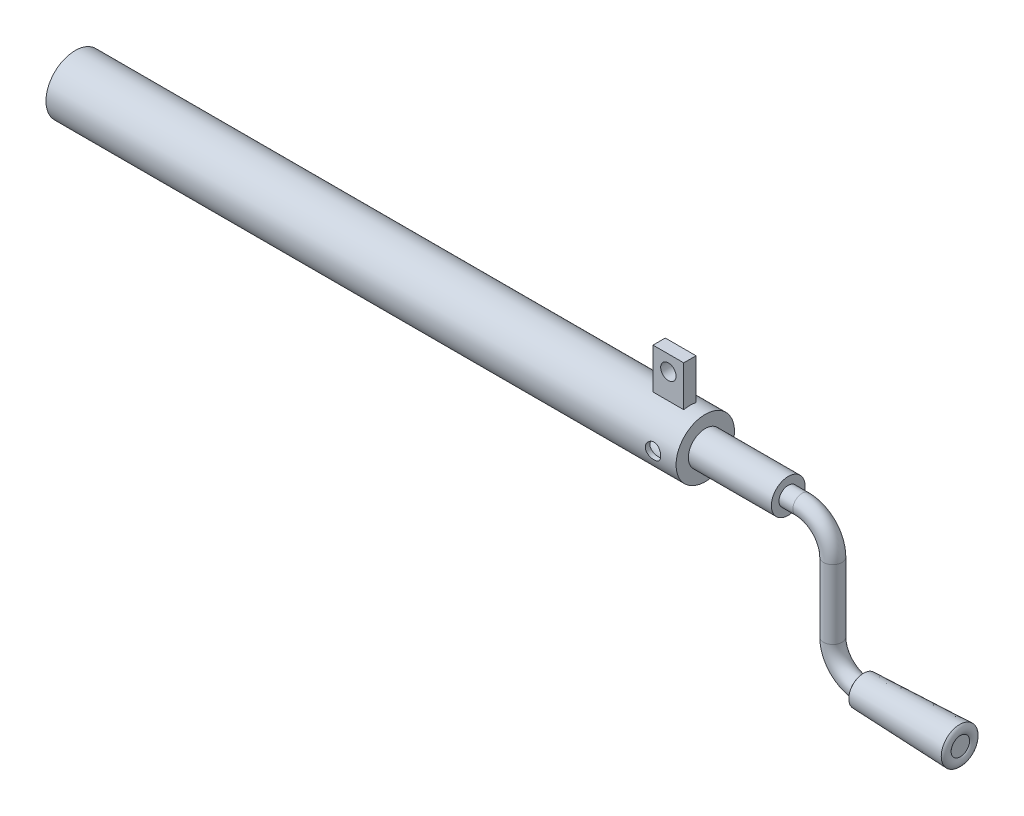
SolidWorks part; units mm, degrees
ref_plane "Front Plane" through (0, 0, 0) normal (0, 0, 1) x (1, 0, 0)
ref_plane "Top Plane" through (0, 0, 0) normal (0, 1, 0) x (1, 0, 0)
ref_plane "Right Plane" through (0, 0, 0) normal (1, 0, 0) x (0, 0, -1)
sketch "Sketch1" plane through (0, 0, 0) normal (1, 0, 0) x (0, 0, -1)
  circle A0 centre (0, 0) radius 19
  circle A1 centre (0, 0) radius 16
  dimension "D1" = 38
  dimension "D2" = 32
extrude "Boss-Extrude1" add sketch "Sketch1" along normal blind 410
sketch "Sketch2" plane through (0, 0, 0) normal (0, 0, 1) x (1, 0, 0)
  line L0 (0, 0) -> (410, 0) construction
  line L1 (410, -19) -> (410, 19) construction
  circle A0 centre (395, 0) radius 5
  dimension "D1" = 10
  dimension "D2" = 15
extrude "Cut-Extrude1" cut sketch "Sketch2" against normal mid plane 60
ref_plane "Plane1" through (0, 45, 0) normal (0, 1, 0) x (1, 0, 0)
sketch "Sketch3" plane through (0, 45, 0) normal (0, 1, 0) x (1, 0, 0)
  line L0 (0, 0) -> (410, 0) construction
  line L1 (410, -19) -> (410, 19) construction
  line L3 (380, 4) -> (400, 4)
  line L4 (380, 4) -> (380, -4)
  line L5 (380, -4) -> (400, -4)
  line L6 (400, 4) -> (400, -4)
  line L7 (380, 4) -> (400, -4) construction
  line L8 (380, -4) -> (400, 4) construction
  point P5 (390, 0)
  point P10 (400, 0)
  dimension "D1" = 8
  dimension "D2" = 20
  dimension "D3" = 10
extrude "Boss-Extrude2" add sketch "Sketch3" against normal up to next
sketch "Sketch4" plane through (0, 0, 4) normal (0, 0, 1) x (1, 0, 0)
  line L0 (390, 45) -> (390, 18.5742) construction
  line L1 (380, 45) -> (400, 45) construction
  line L2 (380, 18.5742) -> (400, 18.5742) construction
  circle A0 centre (390, 35) radius 5
  dimension "D1" = 10
  dimension "D2" = 10
extrude "Cut-Extrude2" cut sketch "Sketch4" against normal blind 10
fillet "Fillet1" [suppressed] radius 5
sketch "Sketch5" plane through (0, 0, 0) normal (0, 0, 1) x (1, 0, 0)
  line L0 (410, 0) -> (473, 0)
  line L1 (410, -19) -> (410, 19) construction
  line L2 (493, -20) -> (493, -65)
  line L3 (513, -85) -> (576, -85)
  arc A0 (493, -65) -> (513, -85) centre (513, -65) ccw
  arc A1 (473, 0) -> (493, -20) centre (473, -20) cw
  point P9 (493, -85)
  dimension "D3" = 20
  dimension "D1" = 83
  dimension "D2" = 85
sweep "Sweep1" add path "Sketch5" circular profile diameter 12 parameters "D3"=12
sketch "Sketch18" plane through (410, 0, 0) normal (1, 0, 0) x (0, 0, -1)
  circle A0 centre (0, 0) radius 16
extrude "Boss-Extrude3" add sketch "Sketch18" against normal blind 10
sketch "Sketch19" plane through (410, 0, 0) normal (1, 0, 0) x (0, 0, -1)
  circle A0 centre (0, 0) radius 11
  dimension "D1" = 22
extrude "Extrude-Thin1" add sketch "Sketch19" along normal blind 54 separate body thin thin type one direction reverse wall 5
sketch "Sketch20" plane through (0, 0, 0) normal (0, 0, 1) x (1, 0, 0)
  line L0 (513, -75.3971) -> (575.5262, -73.0329)
  line L1 (513, -85) -> (587.5162, -85) construction
  line L2 (513, -79) -> (513, -91) construction
  line L3 (576, -79) -> (513, -79) construction
  line L4 (576, -79) -> (513, -79)
  arc A0 (513, -75.3971) -> (513, -79) centre (514.8015, -77.1985) ccw
  arc A1 (575.5262, -73.0329) -> (576, -79) centre (572.794, -76.2522) cw
revolve "Revolve1" add sketch "Sketch20" angle 360 about L1
